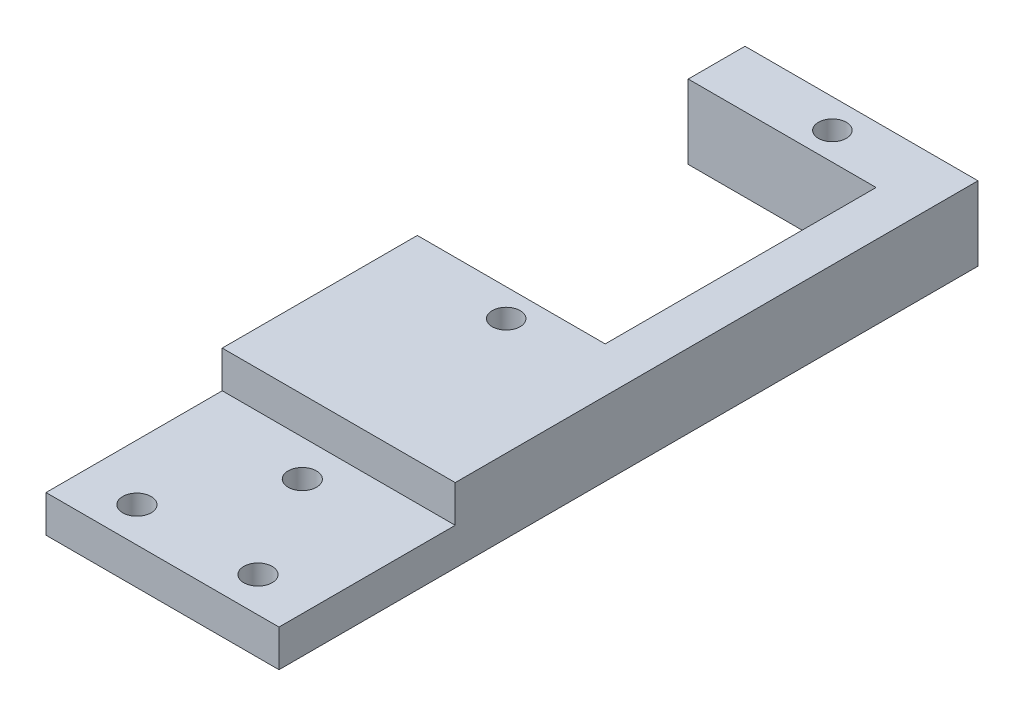
SolidWorks part; units mm, degrees
material "ABS"
ref_plane "Front" through (0, 0, 0) normal (0, 0, 1) x (1, 0, 0)
ref_plane "Top" through (0, 0, 0) normal (0, 1, 0) x (1, 0, 0)
ref_plane "Right" through (0, 0, 0) normal (1, 0, 0) x (0, 0, -1)
sketch "Sketch2" plane through (0, 0, 0) normal (0, 1, 0) x (1, 0, 0)
  line L1 (0, 0) -> (20, 0)
  line L2 (0, 0) -> (0, -60)
  line L3 (0, -60) -> (20, -60)
  line L4 (20, 0) -> (20, -60)
  dimension "D1" = 20
  dimension "D2" = 60
extrude "Boss-Extrude1" add sketch "Sketch2" along normal blind 6.35
sketch "Sketch4" plane through (0, 6.35, 0) normal (0, 1, 0) x (1, 0, 0)
  line L0 (0, 0) -> (0, -60) construction
  line L1 (0, -4.873) -> (16.127, -4.873)
  line L2 (0, -4.873) -> (0, -28.127)
  line L3 (0, -28.127) -> (16.127, -28.127)
  line L4 (16.127, -4.873) -> (16.127, -28.127)
  line L5 (20, -60) -> (20, 0) construction
  line L6 (20, 0) -> (0, 0) construction
  dimension "D1" = 3.873
  dimension "D2" = 4.873
  dimension "D3" = 23.254
extrude "Cut-Extrude1" cut sketch "Sketch4" against normal through all
hole_wizard "M2 Clearance Hole1" positions "Sketch8" profile "Sketch9" hole size "M2" standard "IS"
sketch "Sketch8" plane through (0, 6.35, 0) normal (0, 1, 0) x (1, 0, 0)
  line L0 (10, 0) -> (10, -60) construction
  line L1 (20, 0) -> (0, 0) construction
  line L2 (0, -60) -> (20, -60) construction
  line L3 (0, -28.127) -> (16.127, -28.127) construction
  point P9 (10, -2.5)
  point P11 (10, -30.5)
  dimension "D1" = 2.373
  dimension "D2" = 2.5
sketch "Sketch9" plane through (10, 6.35, 30.5) normal (1, 0, 0) x (0, 0, 1)
  line L0 (0, 0) -> (0, 5.721)
  line L1 (0, 5.721) -> (1.2, 5)
  line L2 (1.2, 5) -> (1.2, 0)
  line L5 (1.2, 0) -> (0, 0)
  line L10 (0, 5.721) -> (-1.2, 5) construction
  line L11 (0, -6.35) -> (0, 107.95) construction
  dimension "Hole Dia." = 2.4
  dimension "Hole Depth" = 5
  dimension "Drill Angle" = 118
sketch "Sketch10" plane through (20, 0, 0) normal (1, 0, 0) x (0, 0, -1)
  line L0 (-60, 6.35) -> (-60, 0) construction
  line L1 (-60, 6.35) -> (-44.873, 6.35)
  line L2 (-60, 6.35) -> (-60, 3.175)
  line L3 (-60, 3.175) -> (-44.873, 3.175)
  line L4 (-44.873, 6.35) -> (-44.873, 3.175)
  dimension "D1" = 15.127
extrude "Cut-Extrude2" cut sketch "Sketch10" against normal through all
sketch "Sketch12" plane through (0, 3.175, 0) normal (0, 1, 0) x (1, 0, 0)
  line L0 (10, -60) -> (10, -44.873) construction
  line L1 (0, -60) -> (20, -60) construction
  line L2 (0, -44.873) -> (20, -44.873) construction
  line L3 (10, -48) -> (15.1962, -57) construction
  line L4 (15.1962, -57) -> (4.8038, -57) construction
  line L5 (4.8038, -57) -> (10, -48) construction
  dimension "D1" = 9
  dimension "D2" = 3
hole_wizard "#2 Clearance Hole1" positions "Sketch13" profile "Sketch14" hole size "#2" standard "ANSI Inch" end condition through all
sketch "Sketch13" plane through (0, 3.175, 0) normal (0, 1, 0) x (1, 0, 0)
  point P0 (10, -48)
  point P3 (4.8038, -57)
  point P6 (15.1962, -57)
sketch "Sketch14" plane through (10, 3.175, 48) normal (1, 0, 0) x (0, 0, 1)
  line L0 (0, 0) -> (0, 3.175)
  line L1 (0, 3.175) -> (1.2192, 3.175)
  line L2 (1.2192, 3.175) -> (1.2192, 0)
  line L5 (1.2192, 0) -> (0, 0)
  line L11 (0, -6.35) -> (0, 107.95) construction
  dimension "Thru Hole Dia." = 2.4384
  dimension "Thru Hole Depth" = 3.175
